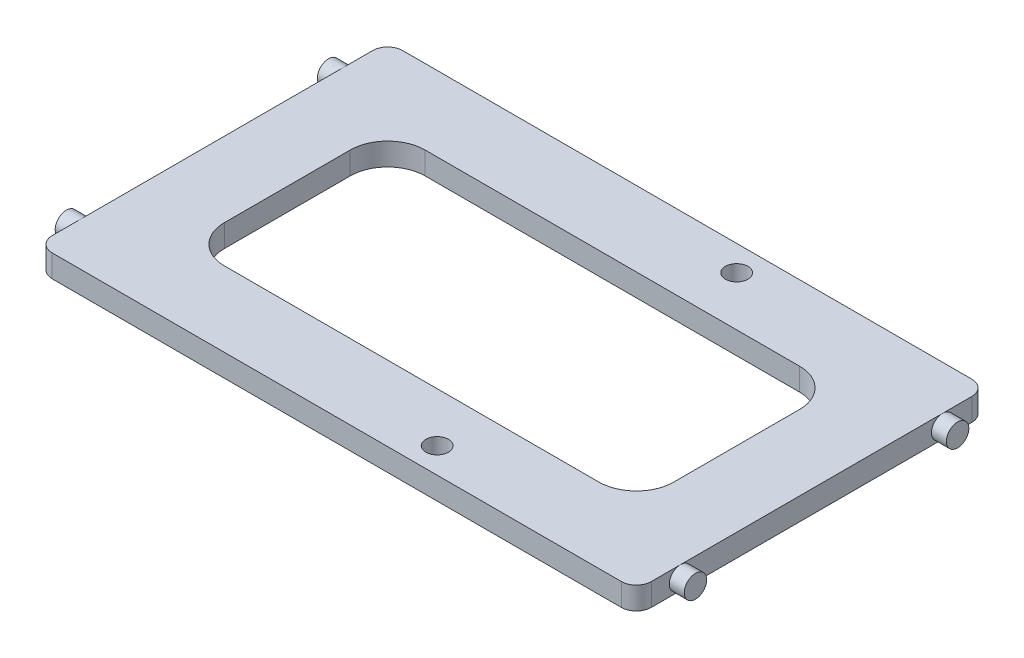
SolidWorks part; units mm, degrees
material "Copper"
ref_plane "Front Plane" through (0, 0, 0) normal (0, 0, 1) x (1, 0, 0)
ref_plane "Top Plane" through (0, 0, 0) normal (0, 1, 0) x (1, 0, 0)
ref_plane "Right Plane" through (0, 0, 0) normal (1, 0, 0) x (0, 0, -1)
sketch "Sketch1" plane through (0, 0, 0) normal (0, 1, 0) x (1, 0, 0)
  line L1 (0, 0) -> (101.6, 0)
  line L2 (0, 0) -> (0, 59.436)
  line L3 (0, 59.436) -> (101.6, 59.436)
  line L4 (101.6, 0) -> (101.6, 59.436)
  dimension "D1" = 59.436
  dimension "D2" = 101.6
extrude "Base Extrude" add sketch "Sketch1" along normal blind 3.81
fillet "Base Corner Fillet" radius 2.54 4 edges at (0, 1.905, 0) (0, 1.905, -59.436) (101.6, 1.905, -59.436) (101.6, 1.905, 0)
sketch "Sketch3" plane through (0, 0, 0) normal (-1, 0, 0) x (0, 0, 1)
  line L0 (-29.718, 3.81) -> (-29.718, 0) construction
  line L1 (-56.896, 3.81) -> (-2.54, 3.81) construction
  line L2 (-56.896, 0) -> (-2.54, 0) construction
  line L3 (0, 1.905) -> (-59.436, 1.905) construction
  line L4 (0, 3.81) -> (0, 0) construction
  line L5 (-59.436, 0) -> (-59.436, 3.81) construction
  circle A0 centre (-7.493, 1.905) radius 1.905
  circle A1 centre (-51.943, 1.905) radius 1.905
  dimension "D1" = 3.81
  dimension "D2" = 22.225
extrude "Peg Extrude" add sketch "Sketch3" along normal blind 2.54 contours A0
ref_plane "Peg Mirror Plane" through (50.8, 0, 0) normal (1, 0, 0) x (0, 0, -1)
mirror "Peg Mirror" about plane through (50.8, 0, 0) normal (1, 0, 0) of "Peg Extrude"
sketch "Sketch4" plane through (0, 0, 0) normal (0, -1, 0) x (1, 0, 0)
  line L0 (2.54, 0) -> (99.06, 0) construction
  line L1 (19.05, -12.7) -> (82.55, -12.7)
  line L2 (12.7, -19.05) -> (12.7, -40.386)
  line L3 (19.05, -46.736) -> (82.55, -46.736)
  line L4 (88.9, -19.05) -> (88.9, -40.386)
  line L5 (99.06, -59.436) -> (2.54, -59.436) construction
  line L6 (0, -51.943) -> (0, -7.493) construction
  line L7 (101.6, -7.493) -> (101.6, -51.943) construction
  arc A0 (82.55, -12.7) -> (88.9, -19.05) centre (82.55, -19.05) cw
  arc A1 (82.55, -46.736) -> (88.9, -40.386) centre (82.55, -40.386) ccw
  arc A2 (12.7, -40.386) -> (19.05, -46.736) centre (19.05, -40.386) ccw
  arc A3 (19.05, -12.7) -> (12.7, -19.05) centre (19.05, -19.05) ccw
  dimension "D5" = 6.35
  dimension "D1" = 12.7
  dimension "D2" = 12.7
  dimension "D3" = 12.7
  dimension "D4" = 12.7
extrude "Material Removal Cut" cut sketch "Sketch4" against normal through all
sketch "Sketch5" plane through (0, 3.81, 0) normal (0, 1, 0) x (1, 0, 0)
  line L0 (0, 29.718) -> (101.6, 29.718) construction
  line L1 (0, 51.943) -> (0, 7.493) construction
  line L2 (101.6, 7.493) -> (101.6, 51.943) construction
  line L3 (63.5, 55.118) -> (63.5, 4.318) construction
  circle A0 centre (63.5, 4.318) radius 1.905
  circle A1 centre (63.5, 55.118) radius 1.905
  point P4 (63.5, 29.718)
  point P5 (0, 0)
  point P13 (71.6808, 4.4962)
  dimension "D1" = 3.81
  dimension "D2" = 50.8
  dimension "D3" = 63.5
extrude "Remote Control Holder Cut" cut sketch "Sketch5" against normal through all
